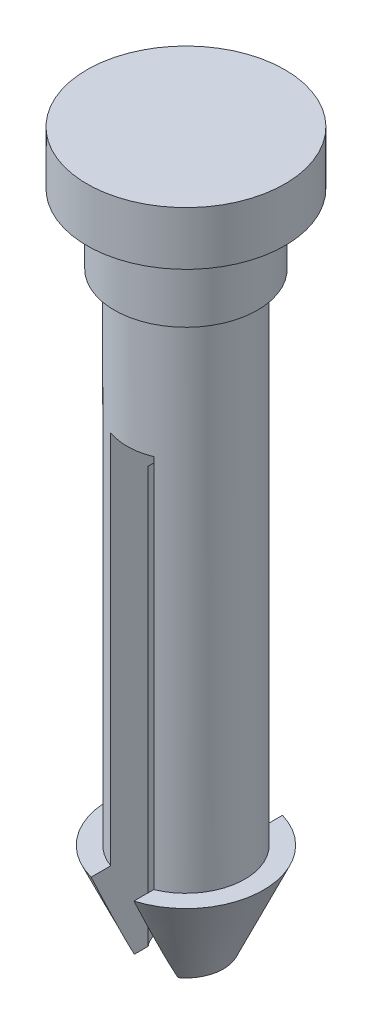
SolidWorks part; units mm, degrees
material "Brass"
ref_plane "Front Plane" through (0, 0, 0) normal (0, 0, 1) x (1, 0, 0)
ref_plane "Top Plane" through (0, 0, 0) normal (0, 1, 0) x (1, 0, 0)
ref_plane "Right Plane" through (0, 0, 0) normal (1, 0, 0) x (0, 0, -1)
sketch "Sketch1" plane through (0, 0, 0) normal (0, 0, 1) x (1, 0, 0)
  line L5 (0, -7) -> (0, 0) construction
  line L6 (1.397, -2.92) -> (1.7, -2.92)
  line L7 (1.7, -2.92) -> (1.6958, -2.9188)
  line L8 (1.7, -1.27) -> (2.3495, -1.27)
  line L118 (2.3495, -1.27) -> (2.3495, 0)
  line L119 (2.3495, 0) -> (0, 0)
  line L122 (1.7, -2.92) -> (1.7, -1.27)
  line L125 (1.397, -14.77) -> (1.397, -2.92)
  line L128 (0.889, -16.87) -> (1.8415, -14.77)
  line L129 (1.8415, -14.77) -> (1.397, -14.77)
  line L133 (0.635, -16.87) -> (0.889, -16.87)
  line L134 (0.635, -16.87) -> (0.635, -7)
  line L135 (0.635, -7) -> (0, -7)
  dimension "D1" = 2.1
  dimension "D2" = 0.762
  dimension "D3" = 13.5
  dimension "D4" = 7
  dimension "D5" = 14.77
revolve "Revolve1" add sketch "Sketch1" angle 360 about L5
sketch "Sketch3" plane through (0, 0, 0) normal (0, 0, 1) x (1, 0, 0)
  line L0 (-0.889, -16.87) -> (0.889, -16.87) construction
  line L1 (-0.4708, -16.87) -> (0.5292, -16.87)
  line L2 (-0.4708, -16.87) -> (-0.4708, -5.87)
  line L3 (-0.4708, -5.87) -> (0.5292, -5.87)
  line L4 (0.5292, -16.87) -> (0.5292, -5.87)
  dimension "D1" = 1
  dimension "D2" = 11
extrude "Cut-Extrude1" cut sketch "Sketch3" against normal through all and the other way through all
